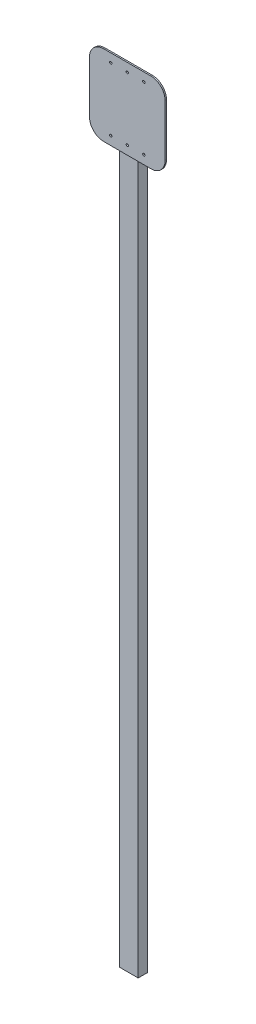
SolidWorks part; units mm, degrees
ref_plane "Alzado" through (0, 0, 0) normal (0, 0, 1) x (1, 0, 0)
ref_plane "Planta" through (0, 0, 0) normal (0, 1, 0) x (1, 0, 0)
ref_plane "Vista lateral" through (0, 0, 0) normal (1, 0, 0) x (0, 0, -1)
sketch "Croquis1" plane through (0, 0, 0) normal (0, 0, 1) x (1, 0, 0)
  line L0 (-50, 85) -> (50, 85)
  line L1 (0, 0) -> (0, 66.75) construction
  line L2 (0, 66.75) -> (0, -66.75) construction
  line L3 (0, 66.75) -> (-35, 66.75) construction
  line L4 (-35, 66.75) -> (35, 66.75) construction
  line L6 (80, 55) -> (80, -55)
  line L7 (50, -85) -> (-50, -85)
  line L8 (-80, 55) -> (-80, -55)
  arc A0 (-80, -55) -> (-50, -85) centre (-50, -55) ccw
  arc A1 (50, -85) -> (80, -55) centre (50, -55) ccw
  circle A2 centre (0, -66.75) radius 2.5
  circle A3 centre (0, 66.75) radius 2.5
  circle A4 centre (-35, 66.75) radius 2.5
  circle A5 centre (35, 66.75) radius 2.5
  circle A6 centre (-35, -66.75) radius 2.5
  circle A7 centre (35, -66.75) radius 2.5
  arc A8 (80, 55) -> (50, 85) centre (50, 55) ccw
  arc A10 (-80, 55) -> (-50, 85) centre (-50, 55) cw
  point P5 (0, 0)
extrude "Saliente-Extruir1" add sketch "Croquis1" along normal blind 3
sketch "Croquis2" plane through (0, 0, 0) normal (0, 0, 1) x (1, 0, 0)
  line L1 (-20, 0) -> (20, 0)
  line L3 (-20, 0) -> (-20, -665)
  line L4 (-20, -84.5148) -> (-20, -1584.5148) construction
  line L5 (20, 0) -> (20, -665)
  line L7 (-20, -1584.5148) -> (20, -1584.5148)
  line L8 (-20, -1584.5148) -> (-20, -665)
  line L10 (20, -1584.5148) -> (20, -665)
extrude "Saliente-Extruir2" add sketch "Croquis2" against normal blind 20
sketch "Croquis3" plane through (0, 0, 0) normal (0, 0, 1) x (1, 0, 0)
  circle A0 centre (0, -66.75) radius 2.5
extrude "Cortar-Extruir1" cut sketch "Croquis3" against normal blind 71 and the other way blind 99
